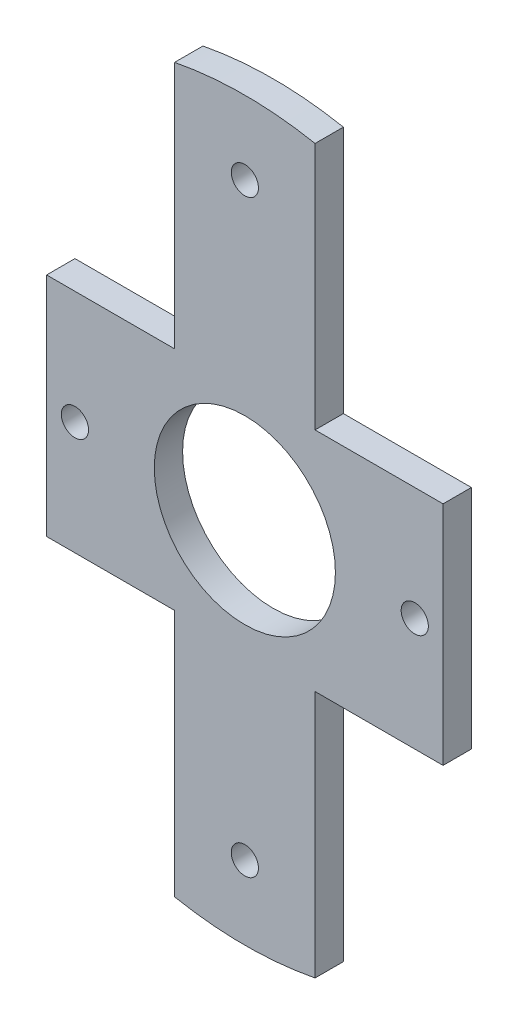
SolidWorks part; units mm, degrees
ref_plane "Front Plane" through (0, 0, 0) normal (0, 0, 1) x (1, 0, 0)
ref_plane "Top Plane" through (0, 0, 0) normal (0, 1, 0) x (1, 0, 0)
ref_plane "Right Plane" through (0, 0, 0) normal (1, 0, 0) x (0, 0, -1)
sketch "Sketch1" plane through (0, 0, 0) normal (0, 0, 1) x (1, 0, 0)
  line L0 (0, 0) -> (0, 65) construction
  line L1 (0, 0) -> (65, 0) construction
  line L2 (12.4, 20) -> (35, 20)
  line L3 (35, 20) -> (35, 0)
  line L4 (12.4, 20) -> (12.4, 63.8063)
  line L5 (-35, 20) -> (-35, -20)
  line L6 (-12.4, 20) -> (-35, 20)
  line L7 (-12.4, 20) -> (-12.4, 63.8063)
  line L8 (12.4, -20) -> (35, -20)
  line L9 (12.4, -20) -> (12.4, -63.8063)
  line L10 (-12.4, -20) -> (-12.4, -63.8063)
  line L11 (-12.4, -20) -> (-35, -20)
  line L12 (35, -20) -> (35, 0)
  arc A0 (-12.4, -63.8063) -> (12.4, -63.8063) centre (0, 0) ccw
  circle A1 centre (0, 0) radius 15.99
  arc A2 (12.4, 63.8063) -> (-12.4, 63.8063) centre (0, 0) ccw
  circle A3 centre (0, 52) radius 2.4
  circle A4 centre (30, 0) radius 2.4
  circle A5 centre (0, -52) radius 2.4
  circle A6 centre (-30, 0) radius 2.4
  point P20 (-35, 0)
  dimension "D1" = 130
  dimension "D2" = 31.98
  dimension "D6" = 4.8
  dimension "D8" = 4.8
  dimension "D3" = 20
  dimension "D4" = 70
  dimension "D5" = 24.8
  dimension "D7" = 52
  dimension "D9" = 30
extrude "Boss-Extrude1" add sketch "Sketch1" along normal blind 5
